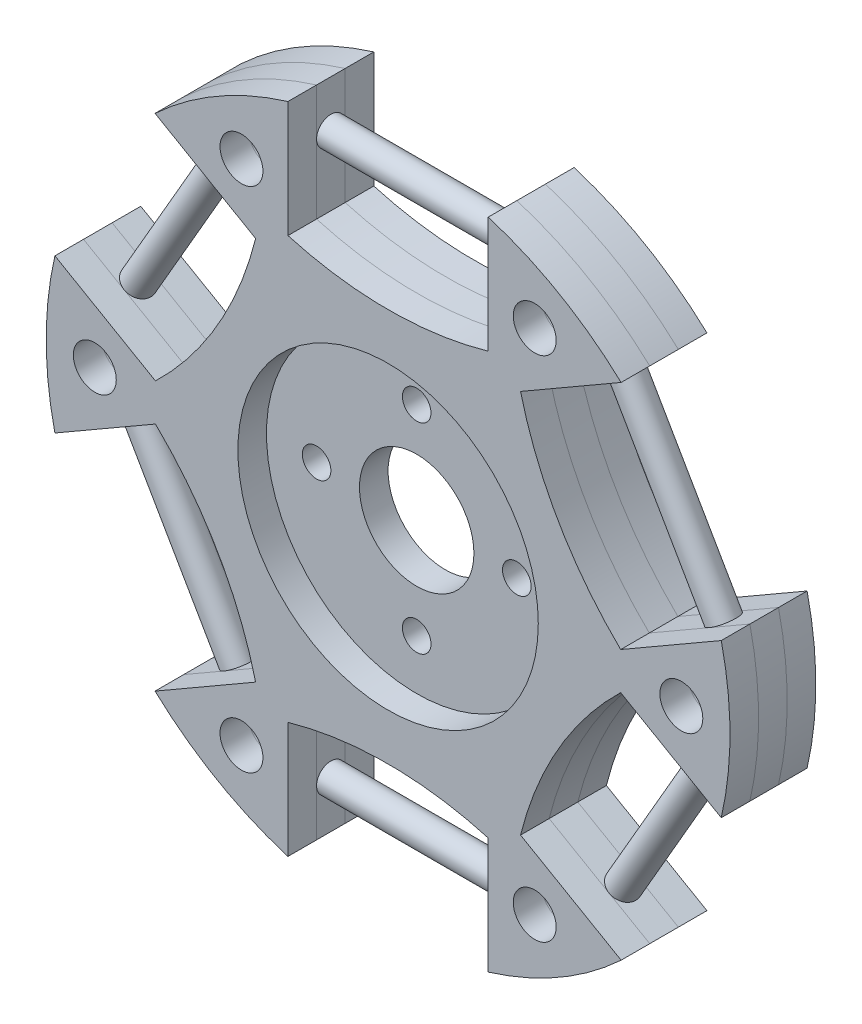
SolidWorks part; units mm, degrees
ref_plane "前视基准面" through (0, 0, 0) normal (0, 0, 1) x (1, 0, 0)
ref_plane "上视基准面" through (0, 0, 0) normal (0, 1, 0) x (1, 0, 0)
ref_plane "右视基准面" through (0, 0, 0) normal (1, 0, 0) x (0, 0, -1)
sketch "草图1" plane through (0, 0, 0) normal (0, 0, 1) x (1, 0, 0)
  circle A0 centre (0, 0) radius 25.4
  circle A1 centre (0, 0) radius 10.5
  dimension "D1" = 50.8
  dimension "D2" = 21
extrude "凸台-拉伸1" add sketch "草图1" along normal blind 2
sketch "草图2" plane through (0, 0, 2) normal (0, 0, 1) x (1, 0, 0)
  circle A0 centre (0, 0) radius 25.4
  circle A1 centre (0, 0) radius 4
  dimension "D1" = 8
extrude "凸台-拉伸2" add sketch "草图2" along normal blind 2 separate body
sketch "草图3" plane through (0, 0, 4) normal (0, 0, 1) x (1, 0, 0)
  circle A0 centre (0, 0) radius 25.4
  circle A1 centre (0, 0) radius 10.5
  dimension "D1" = 21
extrude "凸台-拉伸3" add sketch "草图3" along normal blind 2 separate body
sketch "草图4" plane through (0, 0, 6) normal (0, 0, 1) x (1, 0, 0)
  line L0 (9.2597, 13.429) -> (17.6452, 18.2704)
  line L1 (7, 14.7336) -> (7, 24.4164)
  line L2 (-7, 14.7336) -> (-7, 24.4164)
  line L3 (16.2597, 1.3046) -> (24.6452, 6.146)
  line L4 (16.2597, -1.3046) -> (24.6452, -6.146)
  line L5 (9.2597, -13.429) -> (17.6452, -18.2704)
  line L6 (7, -14.7336) -> (7, -24.4164)
  line L7 (-7, -14.7336) -> (-7, -24.4164)
  line L8 (-9.2597, -13.429) -> (-17.6452, -18.2704)
  line L9 (-16.2597, -1.3046) -> (-24.6452, -6.146)
  line L10 (-16.2597, 1.3046) -> (-24.6452, 6.146)
  line L11 (-9.2597, 13.429) -> (-17.6452, 18.2704)
  arc A0 (7, 24.4164) -> (-7, 24.4164) centre (0, 0) ccw
  arc A1 (9.2597, 13.429) -> (16.2597, 1.3046) centre (33.9049, 19.575) ccw
  arc A2 (-7, 14.7336) -> (7, 14.7336) centre (0, 39.15) ccw
  arc A3 (24.6452, 6.146) -> (17.6452, 18.2704) centre (0, 0) ccw
  arc A4 (16.2597, -1.3046) -> (9.2597, -13.429) centre (33.9049, -19.575) ccw
  arc A5 (17.6452, -18.2704) -> (24.6452, -6.146) centre (0, 0) ccw
  arc A6 (7, -14.7336) -> (-7, -14.7336) centre (0, -39.15) ccw
  arc A7 (-7, -24.4164) -> (7, -24.4164) centre (0, 0) ccw
  arc A8 (-9.2597, -13.429) -> (-16.2597, -1.3046) centre (-33.9049, -19.575) ccw
  arc A9 (-24.6452, -6.146) -> (-17.6452, -18.2704) centre (0, 0) ccw
  arc A10 (-16.2597, 1.3046) -> (-9.2597, 13.429) centre (-33.9049, 19.575) ccw
  arc A11 (-17.6452, 18.2704) -> (-24.6452, 6.146) centre (0, 0) ccw
  point P34 (0, 0)
  dimension "D1" = 50.8
  dimension "D2" = 6
  dimension "D3" = 50.8
extrude "切除-拉伸1" cut sketch "草图4" against normal blind 20.5
sketch "草图5" plane through (0, 0, 6) normal (0, 0, 1) x (1, 0, 0)
  circle A0 centre (0, 0) radius 4 construction
  circle A2 centre (10.25, 17.7535) radius 1.5
  circle A3 centre (20.5, 0) radius 1.5
  circle A4 centre (10.25, -17.7535) radius 1.5
  circle A5 centre (-10.25, -17.7535) radius 1.5
  circle A6 centre (-20.5, 0) radius 1.5
  circle A7 centre (-10.25, 17.7535) radius 1.5
  point P21 (0, 0)
  dimension "D1" = 20.5
  dimension "D2" = 3
  dimension "D3" = 6
extrude "切除-拉伸2" cut sketch "草图5" against normal blind 20.5
sketch "草图6" plane through (-7, 0, 0) normal (1, 0, 0) x (0, 0, -1)
  line L0 (-2, 24.4164) -> (-2, 14.7336) construction
  circle A0 centre (-3, 19.575) radius 1
  dimension "D1" = 2
  dimension "D2" = 1
extrude "凸台-拉伸4" add sketch "草图6" along normal blind 14
pattern_circular "阵列(圆周)1" count 6 over 360 about axis through (0, 0, 6) along (0, 0, 1) of "凸台-拉伸4"
sketch "草图7" plane through (0, 0, 4) normal (0, 0, 1) x (1, 0, 0)
  circle A1 centre (0, 7) radius 1
  circle A2 centre (7, 0) radius 1
  circle A3 centre (0, -7) radius 1
  circle A4 centre (-7, 0) radius 1
  point P14 (0, 0)
  dimension "D2" = 2
  dimension "D3" = 4
extrude "切除-拉伸3" cut sketch "草图7" against normal blind 14
sketch "草图8" plane through (0, 0, 6) normal (0, 0, 1) x (1, 0, 0)
  circle A0 centre (0, 0) radius 23.9
  dimension "D1" = 47.8
extrude "切除-拉伸-薄壁1" cut sketch "草图8" against normal blind 10 thin
